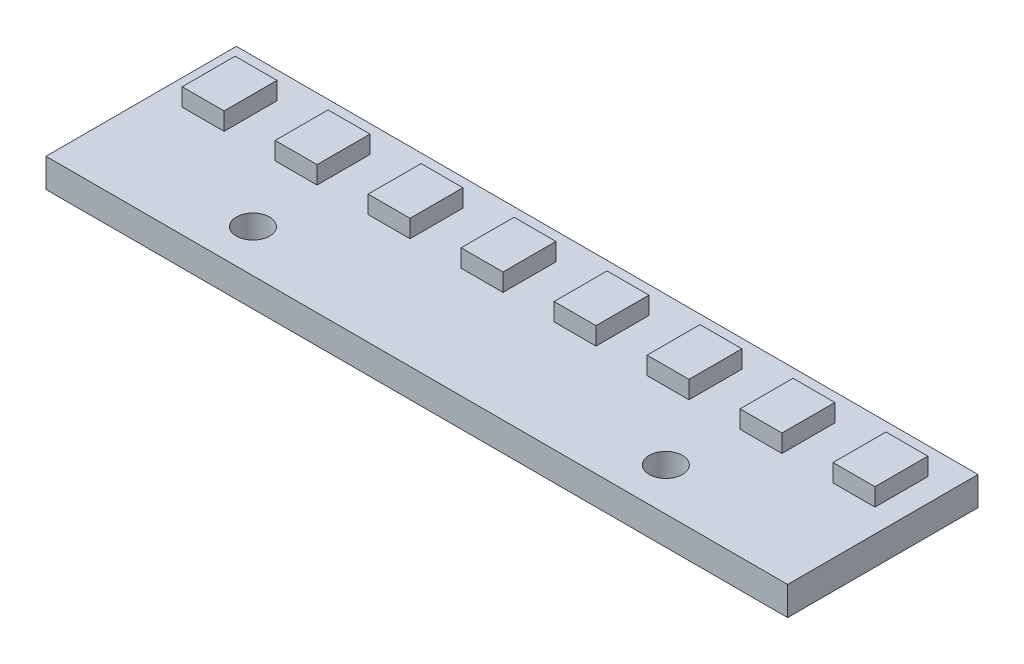
SolidWorks part; units mm, degrees
ref_plane "Front Plane" through (0, 0, 0) normal (0, 0, 1) x (1, 0, 0)
ref_plane "Top Plane" through (0, 0, 0) normal (0, 1, 0) x (1, 0, 0)
ref_plane "Right Plane" through (0, 0, 0) normal (1, 0, 0) x (0, 0, -1)
sketch "Sketch1" plane through (0, 0, 0) normal (0, 1, 0) x (1, 0, 0)
  line L1 (-33.5, 8.6) -> (33.5, 8.6)
  line L2 (-33.5, 8.6) -> (-33.5, -8.6)
  line L3 (-33.5, -8.6) -> (33.5, -8.6)
  line L4 (33.5, 8.6) -> (33.5, -8.6)
  line L5 (-33.5, 8.6) -> (33.5, -8.6) construction
  line L6 (-33.5, -8.6) -> (33.5, 8.6) construction
  point P0 (0, 0)
  dimension "D1" = 17.2
  dimension "D2" = 67
extrude "Boss-Extrude1" add sketch "Sketch1" along normal blind 2.6
sketch "Sketch2" plane through (0, 2.6, 0) normal (0, 1, 0) x (1, 0, 0)
  line L0 (0, -8.6) -> (0, -4.75) construction
  line L1 (-17.15, -8.6) -> (-17.15, -6.25) construction
  line L2 (-33.5, -8.6) -> (33.5, -8.6) construction
  line L3 (17.15, -8.6) -> (17.15, -6.25) construction
  line L4 (-33.5, -4.7908) -> (-20.2, -4.7908) construction
  line L5 (-33.5, 8.6) -> (-33.5, -8.6) construction
  line L6 (33.5, -4.7908) -> (20.2, -4.7908) construction
  line L7 (33.5, -8.6) -> (33.5, 8.6) construction
  line L8 (17.15, 0) -> (18.65, 0) construction
  line L9 (-17.15, 0) -> (-18.65, 0) construction
  line L10 (-18.65, -4.75) -> (18.65, -4.75)
  circle A0 centre (-18.65, 0) radius 1.5
  circle A1 centre (18.65, 0) radius 1.5
  circle A2 centre (-18.65, -4.75) radius 1.5
  circle A3 centre (18.65, -4.75) radius 1.5
  point P4 (0, 0)
  point P27 (0, -4.75)
  dimension "D8" = 3
  dimension "D9" = 3
  dimension "D10" = 3.85
  dimension "D12" = 3
  dimension "D13" = 3
  dimension "D1" = 34.3
  dimension "D2" = 2.35
  dimension "D3" = 2.35
  dimension "D4" = 13.3
  dimension "D5" = 13.3
  dimension "D6" = 1.5
  dimension "D7" = 1.5
  dimension "D11" = 37.3
extrude "Cut-Extrude1" cut sketch "Sketch2" against normal blind 2.6
sketch "Sketch3" plane through (0, 2.6, 0) normal (0, 1, 0) x (1, 0, 0)
  line L0 (-22.7858, 6.1729) -> (-22.7858, 1.3916)
  line L1 (-31.1858, 6.1729) -> (-27.4036, 6.1729)
  line L2 (-31.1858, 6.1729) -> (-31.1858, 1.3916)
  line L3 (-31.1858, 1.3916) -> (-27.4036, 1.3916)
  line L4 (-27.4036, 6.1729) -> (-27.4036, 1.3916)
  line L5 (-22.7858, 6.1729) -> (-19.0036, 6.1729)
  line L6 (-19.0036, 6.1729) -> (-19.0036, 1.3916)
  line L7 (-22.7858, 1.3916) -> (-19.0036, 1.3916)
  line L8 (-14.3858, 6.1729) -> (-14.3858, 1.3916)
  line L9 (-14.3858, 6.1729) -> (-10.6036, 6.1729)
  line L10 (-10.6036, 6.1729) -> (-10.6036, 1.3916)
  line L11 (-14.3858, 1.3916) -> (-10.6036, 1.3916)
  line L12 (-5.9858, 6.1729) -> (-5.9858, 1.3916)
  line L13 (-5.9858, 6.1729) -> (-2.2036, 6.1729)
  line L14 (-2.2036, 6.1729) -> (-2.2036, 1.3916)
  line L15 (-5.9858, 1.3916) -> (-2.2036, 1.3916)
  line L16 (2.4142, 6.1729) -> (2.4142, 1.3916)
  line L17 (2.4142, 6.1729) -> (6.1964, 6.1729)
  line L18 (6.1964, 6.1729) -> (6.1964, 1.3916)
  line L19 (2.4142, 1.3916) -> (6.1964, 1.3916)
  line L20 (10.8142, 6.1729) -> (10.8142, 1.3916)
  line L21 (10.8142, 6.1729) -> (14.5964, 6.1729)
  line L22 (14.5964, 6.1729) -> (14.5964, 1.3916)
  line L23 (10.8142, 1.3916) -> (14.5964, 1.3916)
  line L24 (19.2142, 6.1729) -> (19.2142, 1.3916)
  line L25 (19.2142, 6.1729) -> (22.9964, 6.1729)
  line L26 (22.9964, 6.1729) -> (22.9964, 1.3916)
  line L27 (19.2142, 1.3916) -> (22.9964, 1.3916)
  line L28 (27.6142, 6.1729) -> (27.6142, 1.3916)
  line L29 (27.6142, 6.1729) -> (31.3964, 6.1729)
  line L30 (31.3964, 6.1729) -> (31.3964, 1.3916)
  line L31 (27.6142, 1.3916) -> (31.3964, 1.3916)
  dimension "D1" = 8
extrude "Boss-Extrude2" add sketch "Sketch3" along normal blind 1.6
